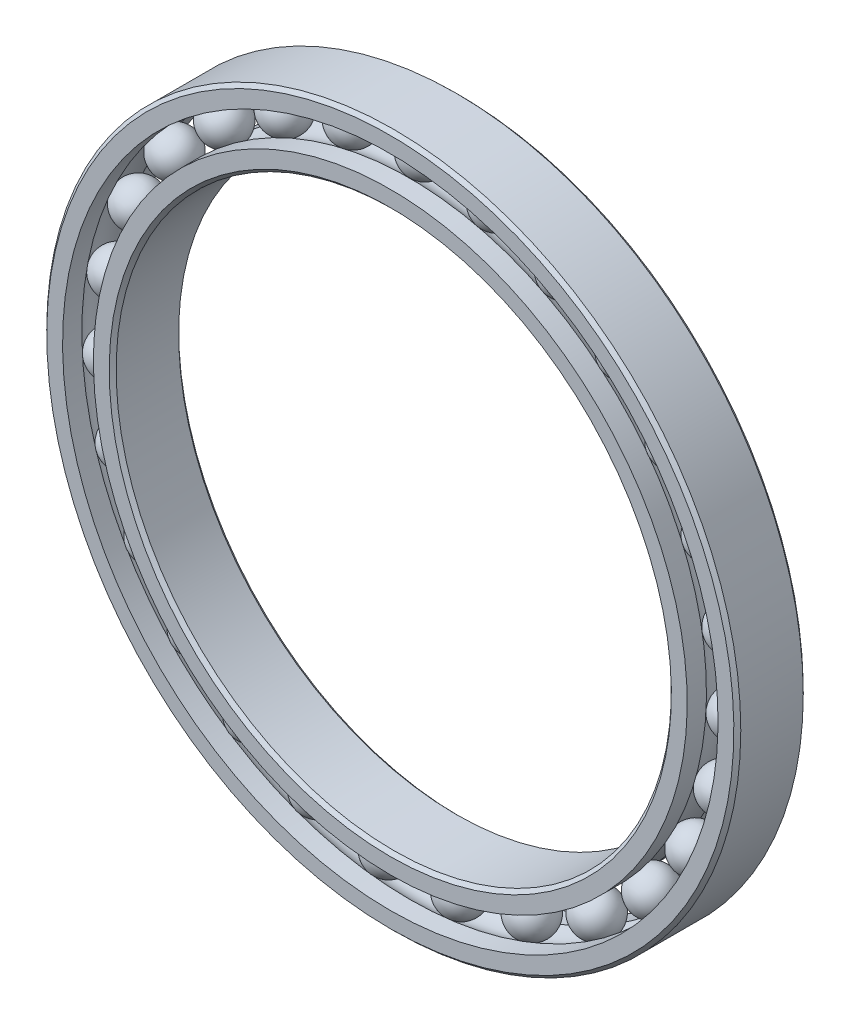
SolidWorks part; units mm, degrees
material "Alloy Steel"
ref_plane "Front Plane" through (0, 0, 0) normal (0, 0, 1) x (1, 0, 0)
ref_plane "Top Plane" through (0, 0, 0) normal (0, 1, 0) x (1, 0, 0)
ref_plane "Right Plane" through (0, 0, 0) normal (1, 0, 0) x (0, 0, -1)
sketch "Sketch1" plane through (0, 0, 0) normal (0, 0, 1) x (1, 0, 0)
  circle A0 centre (0, 0) radius 50
  circle A1 centre (0, 0) radius 40
  dimension "OD" = 100
  dimension "ID" = 80
  dimension "For Shaft Diameter" = 80
  dimension "For Housing ID" = 100
sketch "Sketch8" plane through (0, 0, 0) normal (1, 0, 0) x (0, 0, -1)
  line L1 (-5, 50) -> (5, 50)
  line L2 (-5, 50) -> (-5, -50)
  line L3 (-5, -50) -> (5, -50)
  line L4 (5, 50) -> (5, -50)
  line L5 (-5, 50) -> (5, -50) construction
  line L6 (-5, -50) -> (5, 50) construction
  point P0 (0, 0)
  point P6 (0, -50)
  dimension "Width" = 10
sketch "Sketch5" plane through (0, 0, 0) normal (1, 0, 0) x (0, 0, -1)
  line L0 (-5, 0) -> (5, 0) construction
  line L1 (0, 50) -> (0, -50) construction
  line L2 (4.5, 50) -> (-4.5, 50)
  line L3 (-4.5, 50) -> (-5, 49.5)
  line L4 (-5, 49.5) -> (-5, 47.2222)
  line L5 (-5, 47.2222) -> (-2.2222, 47.2222)
  line L6 (5, 47.2222) -> (2.2222, 47.2222)
  line L7 (5, 49.5) -> (5, 47.2222)
  line L8 (4.5, 50) -> (5, 49.5)
  line L9 (0, 50) -> (0, 45) construction
  line L10 (0, 45) -> (0, 40) construction
  line L11 (-3.1427, 45) -> (-5, 45) construction
  line L22 (0, 50) -> (0, -50) construction
  line L23 (5, 0) -> (5, 50) construction
  line L24 (5, 50) -> (4.5, 50) construction
  line L25 (-5, 0) -> (-5, 50) construction
  line L26 (-5, 50) -> (-4.5, 50) construction
  line L27 (5, 0) -> (5, -50) construction
  line L28 (-5, 0) -> (-5, -50) construction
  line L29 (-5, -50) -> (5, -50) construction
  arc A0 (-2.2222, 47.2222) -> (2.2222, 47.2222) centre (0, 45) cw
  circle A1 centre (0, 45) radius 3.1427 construction
  point P14 (0, 40)
  point P15 (-4.0713, 45)
  dimension "D1" = 45
  dimension "D2" = 0.5
  dimension "D3" = 4.4444
  dimension "D4" = 2.2222
revolve "Revolve1" add sketch "Sketch5" angle 360 about L0
sketch "Sketch3" plane through (0, 0, 0) normal (1, 0, 0) x (0, 0, -1)
  line L0 (-5, 42.7778) -> (-2.2222, 42.7778)
  line L1 (0, 50) -> (0, -50) construction
  line L2 (-5, 49.5) -> (-5, 47.2222) construction
  line L3 (-5, 42.7778) -> (-5, 40.5)
  line L4 (-4.5, 50) -> (-5, 49.5) construction
  line L5 (-5, 40.5) -> (-4.5, 40)
  line L6 (-4.5, 40) -> (4.5, 40)
  line L7 (4.5, 50) -> (4.5, -50) construction
  line L8 (4.5, 40) -> (5, 40.5)
  line L9 (5, -49.5) -> (5, 49.5) construction
  line L10 (5, 40.5) -> (5, 42.7778)
  line L11 (5, 42.7778) -> (2.2222, 42.7778)
  line L13 (4.5, 50) -> (5, 49.5) construction
  arc A0 (2.2222, 47.2222) -> (-2.2222, 47.2222) centre (0, 45) ccw construction
  arc A1 (2.2222, 42.7778) -> (-2.2222, 42.7778) centre (0, 45) cw
revolve "Revolve3" add sketch "Sketch3" angle 360 about L0
sketch "Sketch4" plane through (0, 0, 0) normal (1, 0, 0) x (0, 0, -1)
  line L0 (-3.1427, 45) -> (3.1427, 45)
  arc A2 (-3.1427, 45) -> (3.1427, 45) centre (0, 45) cw
  arc A3 (2.2222, 47.2222) -> (-2.2222, 47.2222) centre (0, 45) ccw construction
revolve "Revolve4" add sketch "Sketch4" angle 360 about L0
pattern_circular "CirPattern1" count 27 every 13.333 about axis through (0, 0, 0) along (0, 0, 1) of bodies 104
equation "\"D2@Sketch5\" = \"Width@Sketch8\" * .05"
equation "\"D3@Sketch5\" = \"Width@Sketch8\" / 2.25"
equation "\"D4@Sketch5\"=((\"OD@Sketch1\"-\"ID@Sketch1\")/2)/4.5"
equation "\"D2@CirPattern1\" = 360/\"Balls@CirPattern1\""
